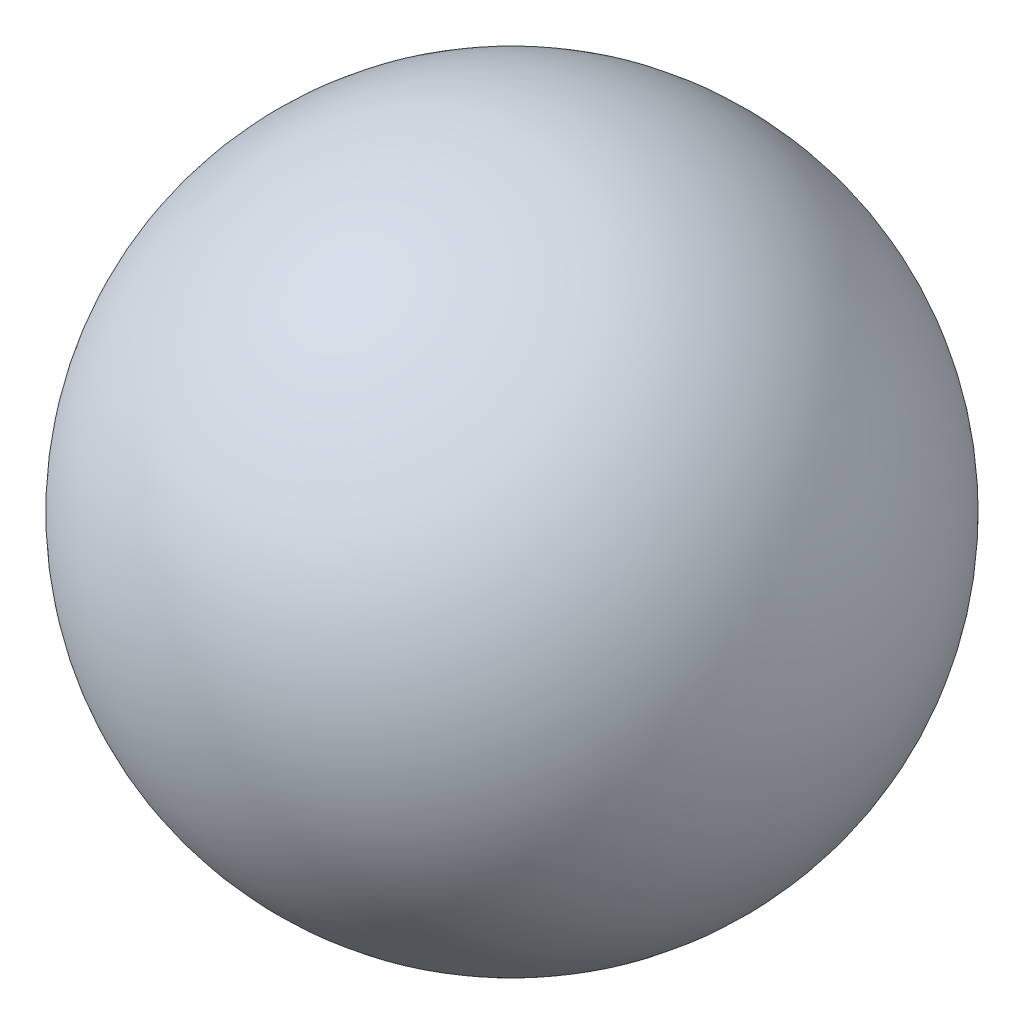
SolidWorks part; units mm, degrees
ref_plane "前视基准面" through (0, 0, 0) normal (0, 0, 1) x (1, 0, 0)
ref_plane "上视基准面" through (0, 0, 0) normal (0, 1, 0) x (1, 0, 0)
ref_plane "右视基准面" through (0, 0, 0) normal (1, 0, 0) x (0, 0, -1)
other "Configuration Table"
sketch "草图1" plane through (0, 0, 0) normal (0, 0, 1) x (1, 0, 0)
  line L0 (0, -1000) -> (0, 49000) construction
  line L1 (0, -120.5) -> (0, 120.5)
  arc A0 (0, 120.5) -> (0, -120.5) centre (0, 0) ccw
  dimension "D1" = 241
revolve "旋转2" add sketch "草图1" angle 360 about L0
